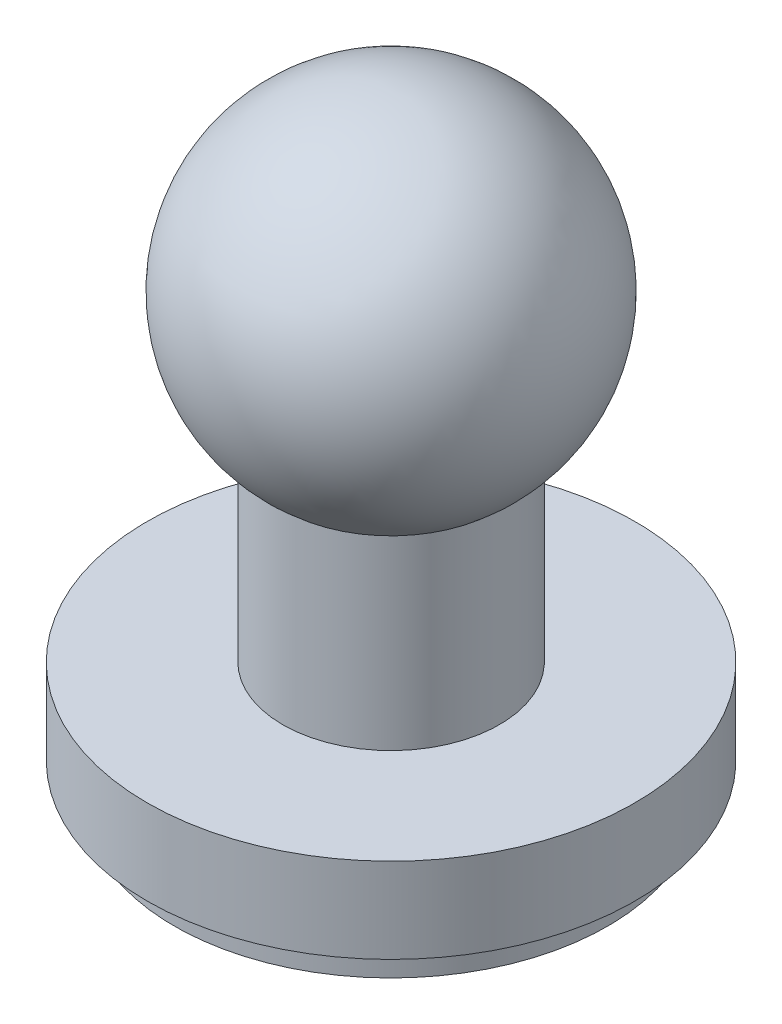
SolidWorks part; units mm, degrees
ref_plane "Front Plane" through (0, 0, 0) normal (0, 0, 1) x (1, 0, 0)
ref_plane "Top Plane" through (0, 0, 0) normal (0, 1, 0) x (1, 0, 0)
ref_plane "Right Plane" through (0, 0, 0) normal (1, 0, 0) x (0, 0, -1)
sketch "Sketch1" plane through (0, 0, 0) normal (0, 1, 0) x (1, 0, 0)
  circle A0 centre (0, 0) radius 4.5
  dimension "D1" = 9
extrude "Boss-Extrude1" add sketch "Sketch1" along normal blind 1.57
sketch "Sketch2" plane through (0, 1.57, 0) normal (0, 1, 0) x (1, 0, 0)
  circle A0 centre (0, 0) radius 2
  dimension "D1" = 4
extrude "Boss-Extrude2" add sketch "Sketch2" along normal blind 5.93
sketch "Sketch3" plane through (0, 7.5, 0) normal (0, 1, 0) x (1, 0, 0)
  line L0 (0, 8.312) -> (0, -16.0573) construction
  line L1 (0, 3.2) -> (0, -3.2)
  arc A0 (0, -3.2) -> (0, 3.2) centre (0, 0) ccw
  dimension "D1" = 3.2
revolve "Revolve1" add sketch "Sketch3" angle 360 about L0
sketch "Sketch4" plane through (0, 0, 0) normal (0, -1, 0) x (1, 0, 0)
  circle A0 centre (0, 0) radius 4
  dimension "D1" = 8
extrude "Boss-Extrude3" add sketch "Sketch4" along normal blind 0.65
ref_point "Point1"
